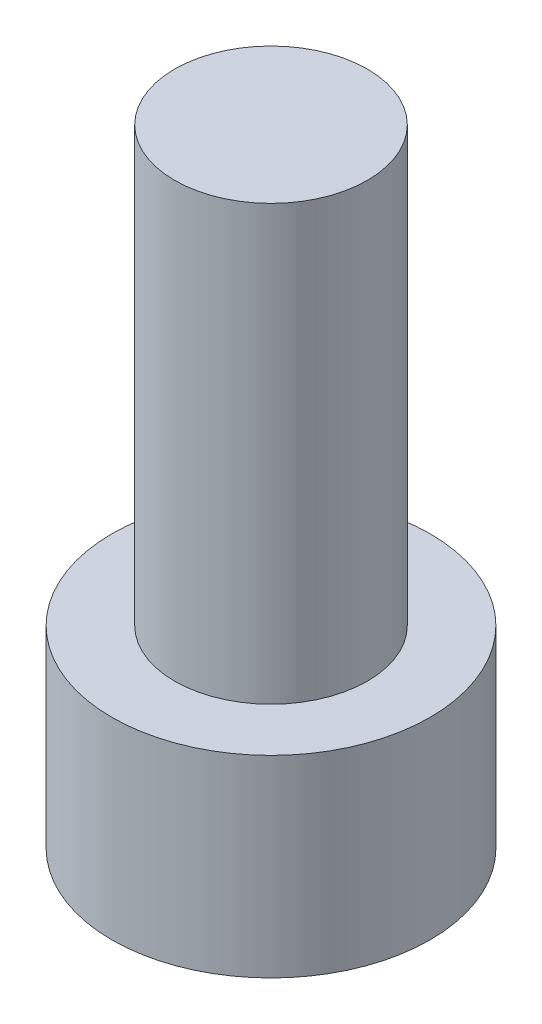
SolidWorks part; units mm, degrees
ref_plane "前视基准面" through (0, 0, 0) normal (0, 0, 1) x (1, 0, 0)
ref_plane "上视基准面" through (0, 0, 0) normal (0, 1, 0) x (1, 0, 0)
ref_plane "右视基准面" through (0, 0, 0) normal (1, 0, 0) x (0, 0, -1)
other "Configuration Table"
sketch "草图1" plane through (0, 0, 0) normal (0, 1, 0) x (1, 0, 0)
  circle A0 centre (0, 0) radius 6.6
  dimension "D1" = 13.2
extrude "凸台-拉伸1" add sketch "草图1" along normal blind 8
sketch "草图2" plane through (0, 8, 0) normal (0, 1, 0) x (1, 0, 0)
  circle A0 centre (0, 0) radius 4
  dimension "D1" = 8
extrude "凸台-拉伸2" add sketch "草图2" along normal blind 18
cosmetic thread "装饰螺纹线1" parameters "D2"=4
sketch "草图3" plane through (0, 0, 0) normal (0, -1, 0) x (1, 0, 0)
  line L1 (3.4606, 0.1554) -> (1.5958, 3.0747)
  line L2 (1.5958, 3.0747) -> (-1.8648, 2.9193)
  line L3 (-1.8648, 2.9193) -> (-3.4606, -0.1554)
  line L4 (-3.4606, -0.1554) -> (-1.5958, -3.0747)
  line L5 (-1.5958, -3.0747) -> (1.8648, -2.9193)
  line L6 (1.8648, -2.9193) -> (3.4606, 0.1554)
  circle A0 centre (0, 0) radius 3 construction
  dimension "D1" = 6
extrude "切除-拉伸1" cut sketch "草图3" against normal blind 4
